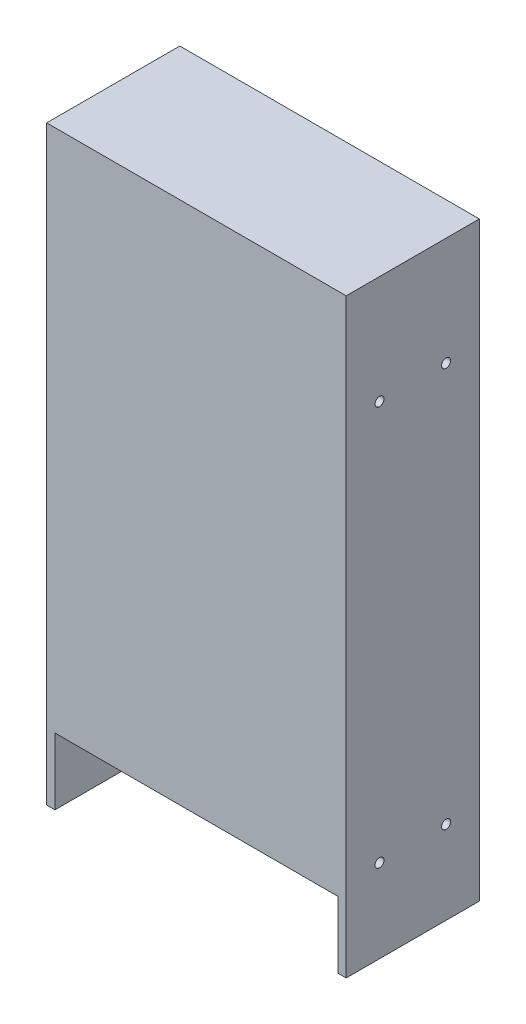
SolidWorks part; units mm, degrees
material "AISI Type 316L stainless steel"
ref_plane "Front Plane" through (0, 0, 0) normal (0, 0, 1) x (1, 0, 0)
ref_plane "Top Plane" through (0, 0, 0) normal (0, 1, 0) x (1, 0, 0)
ref_plane "Right Plane" through (0, 0, 0) normal (1, 0, 0) x (0, 0, -1)
sketch "Sketch1" plane through (0, 0, 0) normal (0, 0, 1) x (1, 0, 0)
  line L1 (-53.6165, 41.1726) -> (60.6835, 41.1726)
  line L2 (-53.6165, 41.1726) -> (-53.6165, -184.2524)
  line L3 (-53.6165, -184.2524) -> (60.6835, -184.2524)
  line L4 (60.6835, 41.1726) -> (60.6835, -184.2524)
  dimension "D1" = 114.3
  dimension "D2" = 225.425
extrude "Boss-Extrude1" add sketch "Sketch1" along normal blind 50.8
sketch "Sketch2" plane through (0, 0, 50.8) normal (0, 0, 1) x (1, 0, 0)
  line L0 (-53.6165, -184.2524) -> (60.6835, -184.2524) construction
  line L1 (-50.4415, -184.2524) -> (57.5085, -184.2524)
  line L2 (-50.4415, -184.2524) -> (-50.4415, -158.8524)
  line L3 (-50.4415, -158.8524) -> (57.5085, -158.8524)
  line L4 (57.5085, -184.2524) -> (57.5085, -158.8524)
  line L5 (-53.6165, 41.1726) -> (-53.6165, -184.2524) construction
  line L6 (60.6835, -184.2524) -> (60.6835, 41.1726) construction
  dimension "D1" = 3.175
  dimension "D2" = 3.175
  dimension "D3" = 25.4
extrude "Cut-Extrude1" cut sketch "Sketch2" against normal blind 38.1
sketch "Sketch4" plane through (60.6835, 0, 0) normal (1, 0, 0) x (0, 0, -1)
  line L0 (0, -184.2524) -> (0, 41.1726) construction
  circle A0 centre (-12.7, -152.5024) radius 1.7145
  circle A2 centre (-38.1, -152.5024) radius 1.7145
  circle A3 centre (-38.1, -0.1024) radius 1.7145
  circle A4 centre (-12.7, -0.1024) radius 1.7145
  dimension "D5" = 3.429
  dimension "D1" = 12.7
  dimension "D2" = 31.75
  dimension "D3" = 2
  dimension "D4" = 2
extrude "Cut-Extrude2" cut sketch "Sketch4" against normal up to surface (114.3 mm away) up to face at (-53.6165, -71.5399, 25.4)
